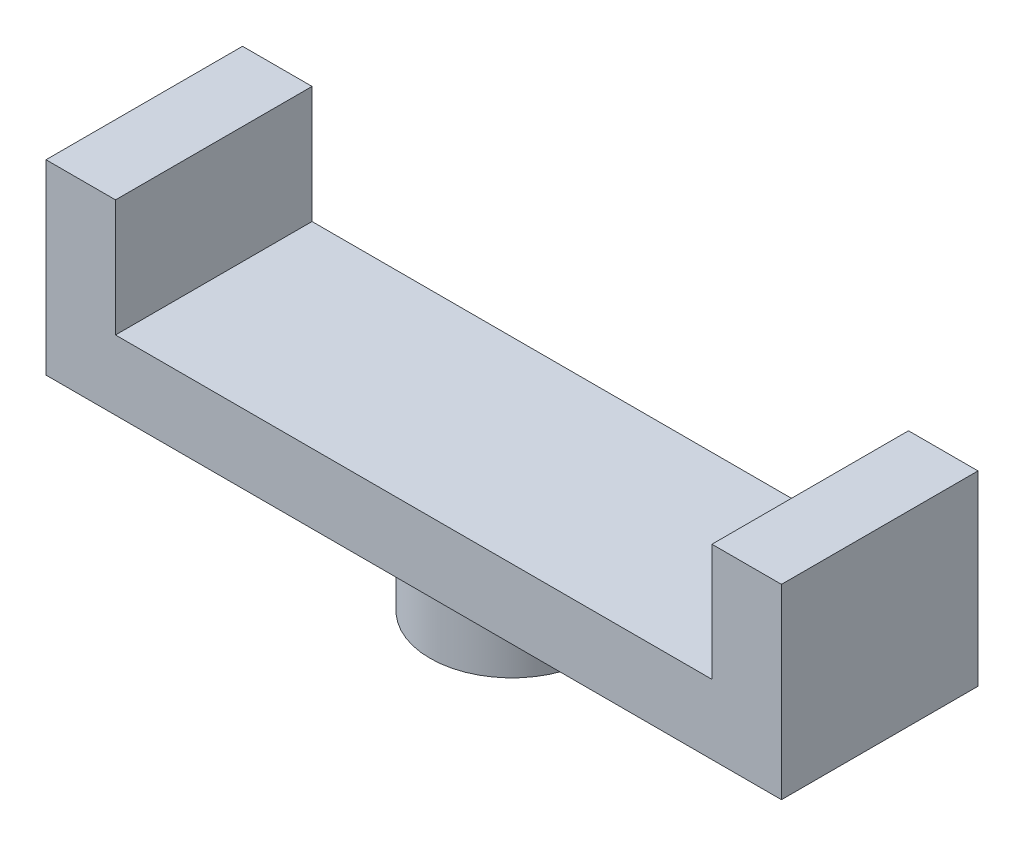
SolidWorks part; units mm, degrees
ref_plane "Front" through (0, 0, 0) normal (0, 0, 1) x (1, 0, 0)
ref_plane "Top" through (0, 0, 0) normal (0, 1, 0) x (1, 0, 0)
ref_plane "Right" through (0, 0, 0) normal (1, 0, 0) x (0, 0, -1)
sketch "Sketch1" plane through (0, 0, 0) normal (0, 1, 0) x (1, 0, 0)
  circle A0 centre (0, 0) radius 5.9
  circle A1 centre (0, 0) radius 2.3
  dimension "D1" = 11.8
  dimension "D2" = 4.6
extrude "Boss-Extrude1" add sketch "Sketch1" along normal blind 5
sketch "Sketch2" plane through (0, 5, 0) normal (0, 1, 0) x (1, 0, 0)
  line L1 (21.45, -7.0679) -> (-21.45, -7.0679)
  line L2 (21.45, -7.0679) -> (21.45, 7.0679)
  line L3 (21.45, 7.0679) -> (-21.45, 7.0679)
  line L4 (-21.45, -7.0679) -> (-21.45, 7.0679)
  line L5 (21.45, -7.0679) -> (-21.45, 7.0679) construction
  line L6 (21.45, 7.0679) -> (-21.45, -7.0679) construction
  point P0 (0, 0)
  dimension "D1" = 42.9
extrude "Boss-Extrude2" add sketch "Sketch2" along normal blind 5 contours L2 L1 L4 L3
sketch "Sketch3" plane through (-21.45, 0, 0) normal (-1, 0, 0) x (0, 0, 1)
  line L1 (-7.0679, 5) -> (7.0679, 5)
  line L2 (-7.0679, 5) -> (-7.0679, 18.4162)
  line L3 (-7.0679, 18.4162) -> (7.0679, 18.4162)
  line L4 (7.0679, 5) -> (7.0679, 18.4162)
extrude "Boss-Extrude3" add sketch "Sketch3" along normal blind 5
mirror "Mirror1" about plane through (0, 0, 0) normal (1, 0, 0) of "Boss-Extrude3"
